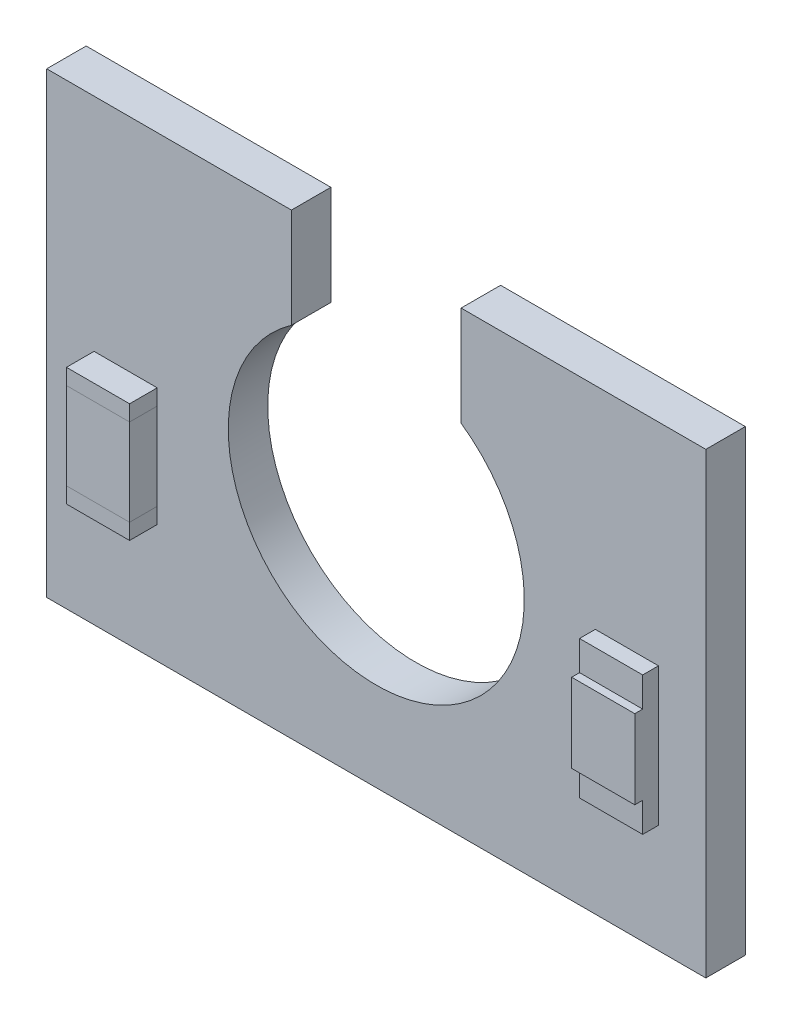
SolidWorks part; units mm, degrees
material "A-Glass Fiber"
ref_plane "Front Plane" through (0, 0, 0) normal (0, 0, 1) x (1, 0, 0)
ref_plane "Top Plane" through (0, 0, 0) normal (0, 1, 0) x (1, 0, 0)
ref_plane "Right Plane" through (0, 0, 0) normal (1, 0, 0) x (0, 0, -1)
sketch "BaseS" plane through (0, 0, 0) normal (0, 0, 1) x (1, 0, 0)
  line L1 (-8.35, 5.8) -> (8.35, 5.8)
  line L2 (-8.35, 5.8) -> (-8.35, -5.8)
  line L3 (-8.35, -5.8) -> (8.35, -5.8)
  line L4 (8.35, 5.8) -> (8.35, -5.8)
  line L5 (-8.35, 5.8) -> (8.35, -5.8) construction
  line L6 (-8.35, -5.8) -> (8.35, 5.8) construction
  point P0 (0, 0)
  dimension "Length" = 11.6
  dimension "Width" = 16.7
extrude "BASE" add sketch "BaseS" against normal blind 1
sketch "FastenerAccessS" plane through (0, 0, 0) normal (0, 0, 1) x (1, 0, 0)
  line L0 (0, -5.8) -> (0, 0.2) construction
  line L1 (-8.35, -5.8) -> (8.35, -5.8) construction
  line L2 (8.35, 5.8) -> (-8.35, 5.8) construction
  line L3 (-2.15, 5.8) -> (2.15, 5.8)
  line L4 (-2.15, 5.8) -> (-2.15, 3.2725)
  line L6 (2.15, 5.8) -> (2.15, 3.2725)
  arc A0 (-2.15, 3.2725) -> (2.15, 3.2725) centre (0, 0.2) ccw
  point P11 (0, 5.8)
  dimension "Dia" = 7.5
  dimension "YLoc" = 6
  dimension "HoleAccessWidth" = 4.3
extrude "FASTENER ACCESS" cut sketch "FastenerAccessS" against normal through all
sketch "SMDCapacitorBodyS" plane through (0, 0, 0) normal (0, 0, 1) x (1, 0, 0)
  line L0 (-8.35, -5.8) -> (8.35, -5.8) construction
  line L1 (-7.15, -0.2) -> (-5.55, -0.2)
  line L2 (-7.15, -0.2) -> (-7.15, -2.4)
  line L3 (-7.15, -2.4) -> (-5.55, -2.4)
  line L4 (-5.55, -0.2) -> (-5.55, -2.4)
  line L5 (-7.15, -0.2) -> (-5.55, -2.4) construction
  line L6 (-7.15, -2.4) -> (-5.55, -0.2) construction
  line L7 (-8.35, 5.8) -> (-8.35, -5.8) construction
  point P0 (-6.35, -1.3)
  dimension "YLoc" = 4.5
  dimension "Width" = 1.6
  dimension "Length" = 2.2
  dimension "XLoc" = 2
extrude "SMD CAPACITOR BODY" add sketch "SMDCapacitorBodyS" along normal blind 0.7 separate body
sketch "SMDCapacitorSolderBody1S" plane through (0, -2.4, 0) normal (0, -1, 0) x (1, 0, 0)
  line L4 (-7.15, 0) -> (-5.55, 0)
  line L5 (-5.55, 0) -> (-5.55, 0.7)
  line L6 (-5.55, 0.7) -> (-7.15, 0.7)
  line L7 (-7.15, 0.7) -> (-7.15, 0)
  line L8 (-7.15, 0) -> (-5.55, 0)
  line L9 (-5.55, 0) -> (-5.55, 0.7)
  line L10 (-5.55, 0.7) -> (-7.15, 0.7)
  line L11 (-7.15, 0.7) -> (-7.15, 0)
  dimension "D1" = 0
extrude "SMD CAPACITOR SOLDER BODY 1" add sketch "SMDCapacitorSolderBody1S" along normal blind 0.4 separate body
sketch "SMDCapacitorSolderBody2S" plane through (0, -0.2, 0) normal (0, 1, 0) x (1, 0, 0)
  line L4 (-5.55, 0) -> (-7.15, 0)
  line L5 (-7.15, 0) -> (-7.15, -0.7)
  line L6 (-7.15, -0.7) -> (-5.55, -0.7)
  line L7 (-5.55, -0.7) -> (-5.55, 0)
  line L8 (-5.55, 0) -> (-7.15, 0)
  line L9 (-7.15, 0) -> (-7.15, -0.7)
  line L10 (-7.15, -0.7) -> (-5.55, -0.7)
  line L11 (-5.55, -0.7) -> (-5.55, 0)
  dimension "D1" = 0
extrude "SMD CAPACITOR SOLDER BODY 2" add sketch "SMDCapacitorSolderBody2S" along normal blind 0.4 separate body
sketch "LEDS" plane through (0, 0, 0) normal (0, 0, 1) x (1, 0, 0)
  line L0 (-6.35, -1.3) -> (6.35, -1.3) construction
  line L1 (5.55, 0.45) -> (7.15, 0.45)
  line L2 (5.55, 0.45) -> (5.55, -3.05)
  line L3 (5.55, -3.05) -> (7.15, -3.05)
  line L4 (7.15, 0.45) -> (7.15, -3.05)
  line L5 (5.55, 0.45) -> (7.15, -3.05) construction
  line L6 (5.55, -3.05) -> (7.15, 0.45) construction
  line L7 (0, 0) -> (0, -1.3) construction
  point P0 (6.35, -1.3)
  dimension "Width" = 1.6
  dimension "Length" = 3.5
extrude "LED" add sketch "LEDS" along normal blind 0.4 separate body
sketch "LEDTS" plane through (0, 0, 0.4) normal (0, 0, 1) x (1, 0, 0)
  line L0 (7.15, -3.05) -> (7.15, 0.45) construction
  line L1 (5.55, -0.3) -> (7.15, -0.3)
  line L2 (5.55, -0.3) -> (5.55, -2.3)
  line L3 (5.55, -2.3) -> (7.15, -2.3)
  line L4 (7.15, -0.3) -> (7.15, -2.3)
  line L5 (5.55, -0.3) -> (7.15, -2.3) construction
  line L6 (5.55, -2.3) -> (7.15, -0.3) construction
  point P0 (6.35, -1.3)
  dimension "Length" = 2
extrude "LED TOP" add sketch "LEDTS" along normal blind 0.2
